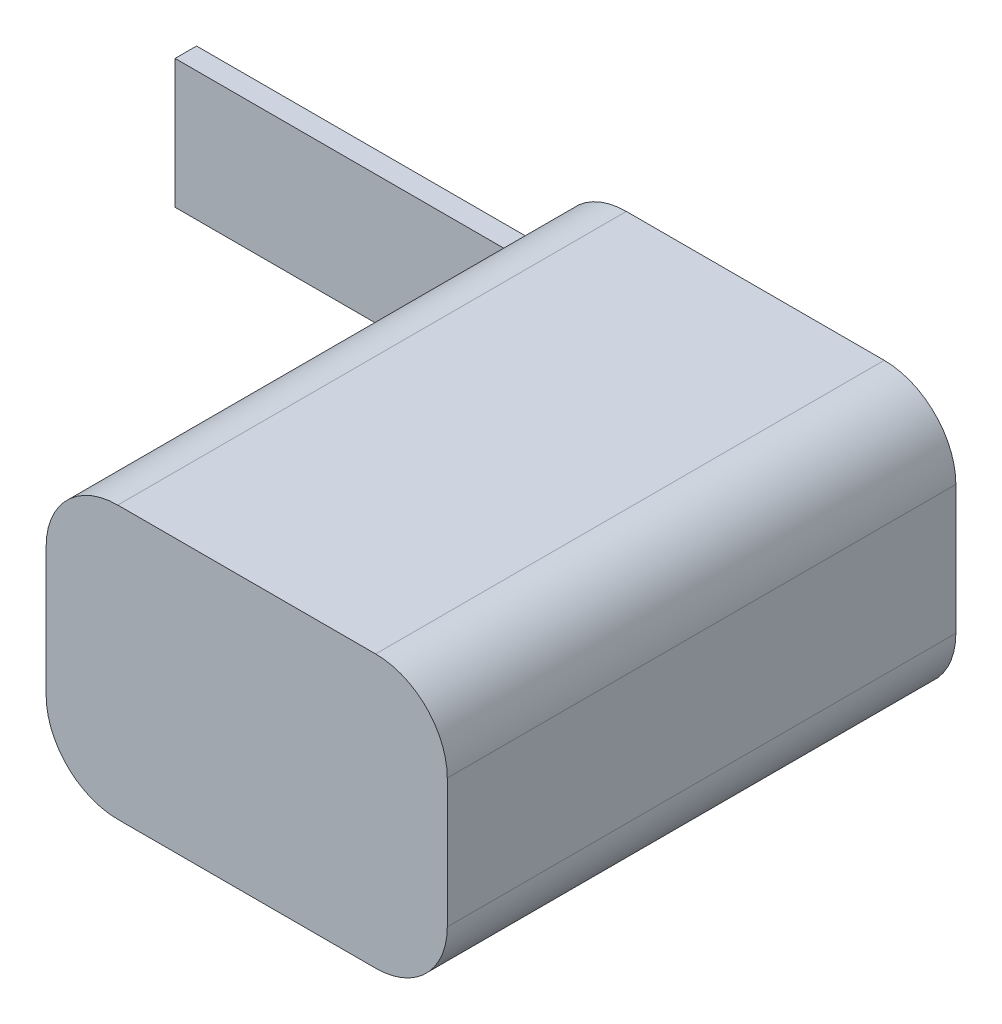
SolidWorks part; units mm, degrees
ref_plane "前视基准面" through (0, 0, 0) normal (0, 0, 1) x (1, 0, 0)
ref_plane "上视基准面" through (0, 0, 0) normal (0, 1, 0) x (1, 0, 0)
ref_plane "右视基准面" through (0, 0, 0) normal (1, 0, 0) x (0, 0, -1)
other "Configuration Table"
sketch "草图1" plane through (0, 0, 0) normal (0, 0, 1) x (1, 0, 0)
  line L1 (0, 0) -> (56, 0)
  line L2 (0, 0) -> (0, 38)
  line L3 (0, 38) -> (56, 38)
  line L4 (56, 0) -> (56, 38)
  dimension "D1" = 56
  dimension "D2" = 38
extrude "凸台-拉伸1" add sketch "草图1" along normal blind 71
fillet "圆角1" radius 10 4 edges at (56, 0, 35.5) (0, 0, 35.5) (0, 38, 35.5) (56, 38, 35.5)
sketch "草图2" plane through (0, 0, 0) normal (-1, 0, 0) x (0, 0, 1)
  line L0 (0, 10) -> (71, 10) construction
  line L1 (0, 28) -> (3, 28)
  line L2 (0, 28) -> (0, 10)
  line L3 (0, 10) -> (3, 10)
  line L4 (3, 28) -> (3, 10)
  dimension "D1" = 3
extrude "凸台-拉伸2" add sketch "草图2" along normal blind 50
